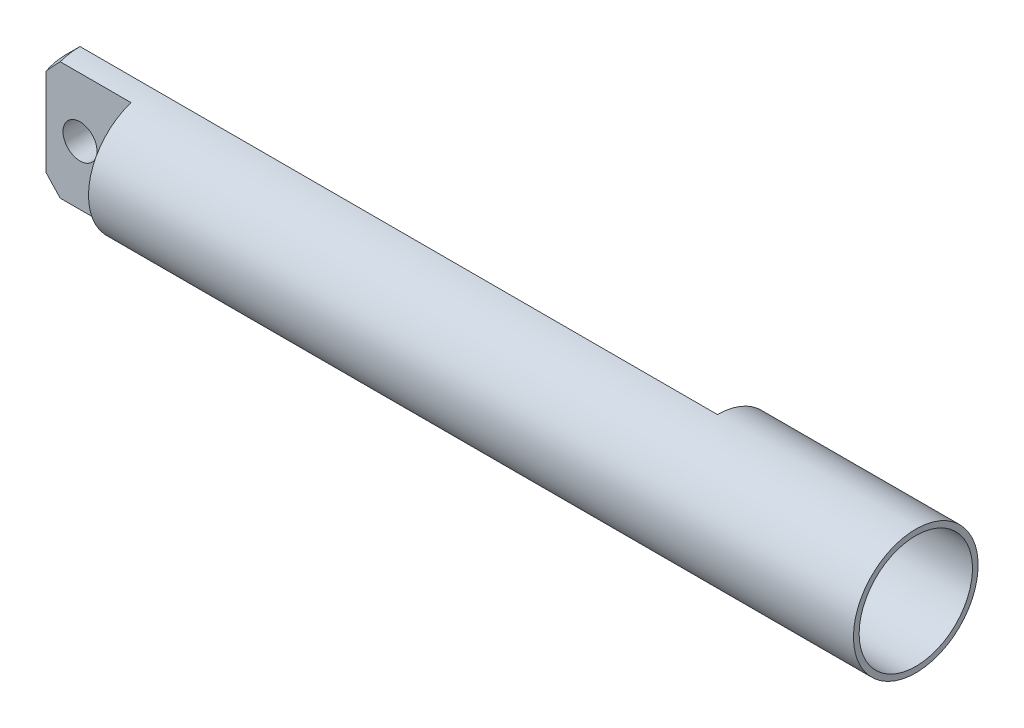
SolidWorks part; units mm, degrees
ref_plane "Plan de face" through (0, 0, 0) normal (0, 0, 1) x (1, 0, 0)
ref_plane "Plan de dessus" through (0, 0, 0) normal (0, 1, 0) x (1, 0, 0)
ref_plane "Plan de droite" through (0, 0, 0) normal (1, 0, 0) x (0, 0, -1)
sketch "Esquisse1" plane through (0, 0, 0) normal (0, 1, 0) x (1, 0, 0)
  line L0 (0, 0) -> (183.3627, 0) construction
  line L1 (0, 0) -> (0, 22)
  line L2 (0, 22) -> (300, 22)
  line L3 (300, 22) -> (300, 20)
  line L4 (300, 20) -> (40, 20)
  line L5 (40, 20) -> (40, 0)
  line L6 (0, 0) -> (40, 0)
  dimension "D1" = 40
  dimension "D2" = 44
  dimension "D3" = 40
  dimension "D4" = 300
revolve "Révolution1" add sketch "Esquisse1" angle 360 about L0
chamfer "Chanfrein1" distance 5 angle 45 1 edges at (0, 0, 22)
sketch "Esquisse2" plane through (0, 0, 0) normal (0, 1, 0) x (1, 0, 0)
  line L0 (0, 0) -> (201.9795, 0) construction
  line L1 (-32.3055, 7) -> (30, 7)
  line L2 (-32.3055, 7) -> (-32.3055, 37.2895)
  line L3 (-32.3055, 37.2895) -> (30, 37.2895)
  line L4 (30, 7) -> (30, 37.2895)
  line L5 (30, -7) -> (30, -37.2895)
  line L6 (-32.3055, -37.2895) -> (30, -37.2895)
  line L7 (-32.3055, -7) -> (-32.3055, -37.2895)
  line L8 (-32.3055, -7) -> (30, -7)
  line L9 (0, 22) -> (0, -22) construction
  dimension "D1" = 14
  dimension "D2" = 30
extrude "Enlèv. mat.-Extru.1" cut sketch "Esquisse2" against normal mid plane 50
sketch "Esquisse3" plane through (0, 0, -7) normal (0, 0, -1) x (-1, 0, 0)
  line L0 (0, 15.4919) -> (0, -15.4919) construction
  circle A0 centre (-12, 0) radius 6
  dimension "D1" = 12
  dimension "D2" = 12
extrude "Enlèv. mat.-Extru.2" cut sketch "Esquisse3" against normal up to next
sketch "Esquisse4" plane through (0, 0, 0) normal (1, 0, 0) x (0, 0, -1)
  line L1 (39.2358, 28.1356) -> (0, 28.1356)
  line L2 (39.2358, 28.1356) -> (39.2358, 0)
  line L3 (39.2358, 0) -> (0, 0)
  line L4 (0, 28.1356) -> (0, 0)
extrude "Enlèv. mat.-Extru.3" cut sketch "Esquisse4" along normal blind 230
